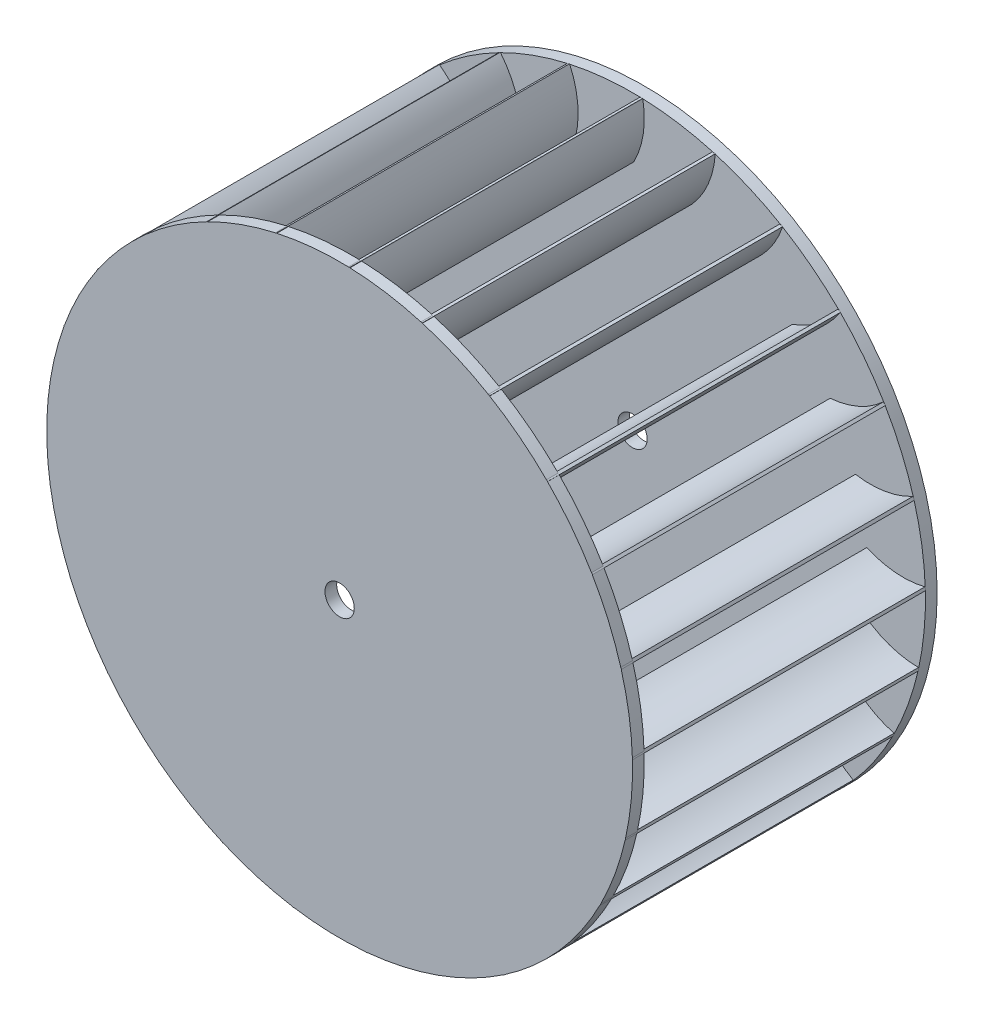
SolidWorks part; units mm, degrees
material "6061 Alloy"
ref_plane "Front Plane" through (0, 0, 0) normal (0, 0, 1) x (1, 0, 0)
ref_plane "Top Plane" through (0, 0, 0) normal (0, 1, 0) x (1, 0, 0)
ref_plane "Right Plane" through (0, 0, 0) normal (1, 0, 0) x (0, 0, -1)
sketch "Sketch1" plane through (0, 0, 0) normal (0, 0, 1) x (1, 0, 0)
  circle A0 centre (0, 0) radius 500
  circle A1 centre (0, 0) radius 25
  dimension "D1" = 1000
  dimension "D2" = 50
extrude "Boss-Extrude1" add sketch "Sketch1" along normal blind 20 contours A0 | A1
sketch "Sketch2" plane through (0, 0, 20) normal (0, 0, 1) x (1, 0, 0)
  arc A0 (15, 499.7749) -> (0, 399.7749) centre (-137.4011, 471.5101) cw
  circle A7 centre (0, 0) radius 500 construction
  dimension "D3" = 155
  dimension "D1" = 100
  dimension "D2" = 15
extrude "Extrude-Thin1" add sketch "Sketch2" along normal blind 500 thin thin type mid plane wall 5
sketch "Sketch3" plane through (0, 0, 20) normal (0, 0, -1) x (-1, 0, 0)
  line L0 (-17.4581, 500.2308) -> (-17.5571, 499.6917)
  line L2 (-17.4581, 500.2308) -> (-15, 499.7749)
extrude "Cut-Extrude1" cut sketch "Sketch3" against normal blind 500 and the other way through all
pattern_circular "CirPattern1" count 25 over 360 about axis through (0, 0, 0) along (0, 0, 1) of "Extrude-Thin1"
sketch "Sketch4" plane through (0, 0, 520) normal (0, 0, 1) x (1, 0, 0)
  circle A1 centre (0, 0) radius 25
  circle A2 centre (0, 0) radius 25
  circle A3 centre (0, 0) radius 500
  circle A4 centre (0, 0) radius 500
  dimension "D1" = 0
  dimension "D2" = 0
extrude "Boss-Extrude2" add sketch "Sketch4" against normal blind 20
